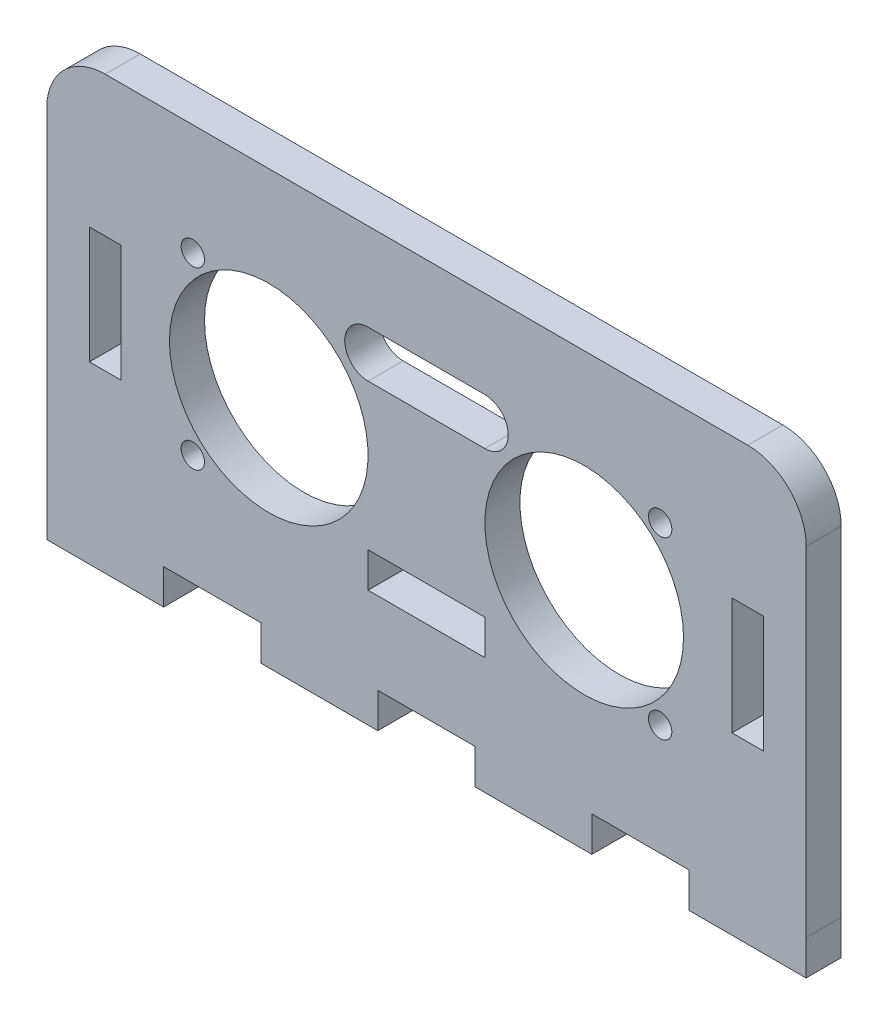
SolidWorks part; units mm, degrees
ref_plane "Front Plane" through (0, 0, 0) normal (0, 0, 1) x (1, 0, 0)
ref_plane "Top Plane" through (0, 0, 0) normal (0, 1, 0) x (1, 0, 0)
ref_plane "Right Plane" through (0, 0, 0) normal (1, 0, 0) x (0, 0, -1)
sketch "Sketch1" plane through (0, 0, 0) normal (0, 0, 1) x (1, 0, 0)
  line L0 (-22.5, 41.49) -> (-22.5, -23.7132) construction
  line L1 (0, 0) -> (-45, 0) construction
  line L2 (0, 0) -> (0, 20) construction
  line L3 (0, 20) -> (-45, 20) construction
  line L4 (-45, 0) -> (-45, 20) construction
  line L5 (-18.34, -7) -> (-26.67, -7)
  line L6 (-27.5, 17.5) -> (-17.5, 17.5) construction
  line L7 (-27.5, 19.5) -> (-17.5, 19.5)
  line L8 (-27.5, 15.5) -> (-17.5, 15.5)
  line L9 (10, -7) -> (9.99, -7)
  line L10 (-17.5, 3) -> (-27.5, 3)
  line L11 (-17.5, 3) -> (-17.5, 0)
  line L12 (-17.5, 0) -> (-27.5, 0)
  line L13 (-27.5, 3) -> (-27.5, 0)
  line L14 (-26.67, -7) -> (-26.67, -10)
  line L15 (10, -7) -> (10, 27)
  line L16 (10, 27) -> (-55, 27)
  line L17 (-55, -7) -> (-55, 27)
  line L18 (-48.65, 5) -> (-48.65, 15)
  line L19 (-55, -7) -> (-55, -10)
  line L20 (-55, -10) -> (-45, -10)
  line L21 (-45, -7) -> (-45, -10)
  line L22 (-36.67, -10) -> (-26.67, -10)
  line L23 (-36.67, -7) -> (-36.67, -10)
  line L24 (-8.34, -7) -> (-8.34, -10)
  line L25 (-18.34, -10) -> (-8.34, -10)
  line L26 (-18.34, -7) -> (-18.34, -10)
  line L27 (9.99, -7) -> (9.99, -10)
  line L28 (-0.01, -10) -> (9.99, -10)
  line L29 (-0.01, -7) -> (-0.01, -10)
  line L30 (-0.01, -7) -> (-8.34, -7)
  line L32 (-36.67, -7) -> (-45, -7)
  line L33 (-48.65, 15) -> (-51.35, 15)
  line L34 (-51.35, 15) -> (-51.35, 5)
  line L35 (-48.65, 5) -> (-51.35, 5)
  line L36 (3.65, 5) -> (6.35, 5)
  line L37 (6.35, 15) -> (6.35, 5)
  line L38 (3.65, 15) -> (6.35, 15)
  line L39 (3.65, 5) -> (3.65, 15)
  line L40 (14.1961, 10) -> (-78.0888, 10) construction
  circle A0 centre (-42.5, 17.5) radius 1
  circle A1 centre (-9, 10) radius 8.5
  circle A2 centre (-36, 10) radius 8.5
  circle A3 centre (-2.5, 17.5) radius 1
  circle A4 centre (-2.5, 2.5) radius 1
  circle A5 centre (-42.5, 2.5) radius 1
  arc A6 (-27.5, 19.5) -> (-27.5, 15.5) centre (-27.5, 17.5) ccw
  arc A7 (-17.5, 15.5) -> (-17.5, 19.5) centre (-17.5, 17.5) ccw
  point P23 (-22.5, 17.5)
  point P32 (10, 10)
  point P38 (10, 10)
  point P39 (-55, 10)
  point P42 (0, 27)
  point P43 (10, 20)
  point P56 (-51.35, 10)
  point P60 (-50, 5)
  point P62 (-48.65, 10)
  point P63 (-55, 5)
  dimension "D5" = 2
  dimension "D9" = 17
  dimension "D1" = 45
  dimension "D2" = 20
  dimension "D3" = 2.5
  dimension "D4" = 2.5
  dimension "D6" = 13.5
  dimension "D7" = 22.5
  dimension "D8" = 17
  dimension "D10" = 10
  dimension "D11" = 5
  dimension "D12" = 4
  dimension "D13" = 5
  dimension "D14" = 10
  dimension "D15" = 17
  dimension "D16" = 10
  dimension "D17" = 10
  dimension "D18" = 7
  dimension "D19" = 10
  dimension "D20" = 3
  dimension "D22" = 0.01
  dimension "D23" = 3
  dimension "D24" = 10
  dimension "D25" = 2.7
  dimension "D26" = 5
  dimension "D21" = 4
extrude "Boss-Extrude1" add sketch "Sketch1" along normal blind 3
fillet "Fillet1" radius 5 2 edges at (10, 27, 1.5) (-55, 27, 1.5)
